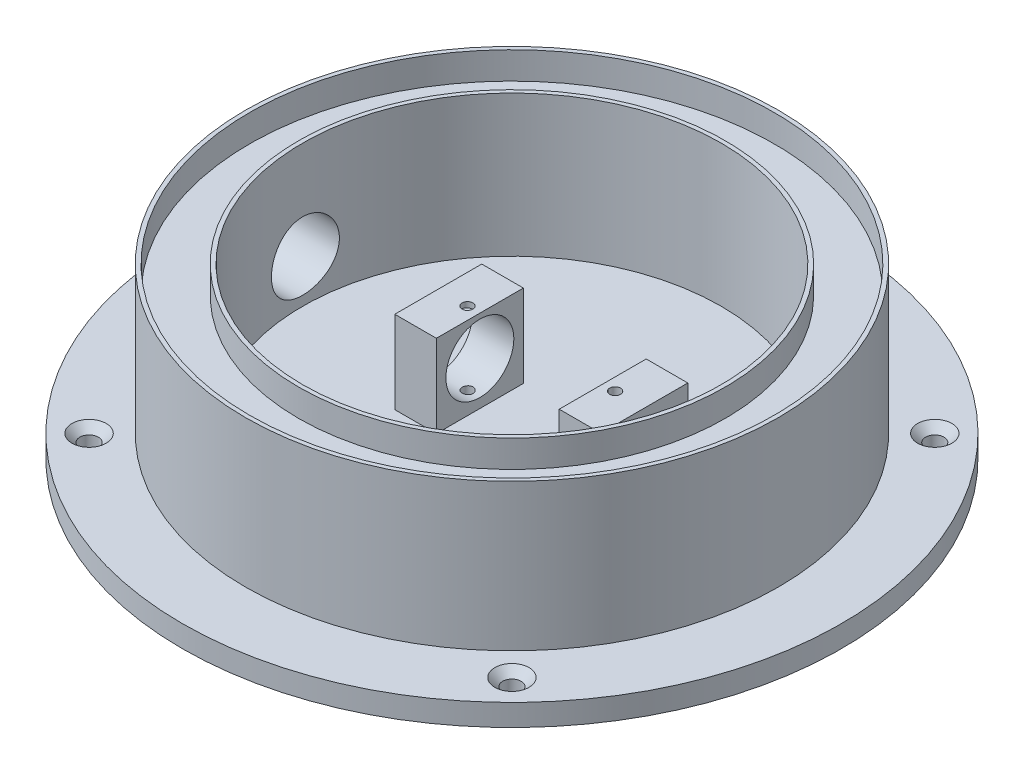
SolidWorks part; units mm, degrees
other "Markup1"
sketch "Sketch25" plane through (60.625, 46, 60.625) normal (0.2544, 0.6682, 0.6991) x (0.7838, 0.2809, -0.5538)
ref_plane "Front Plane" through (0, 0, 0) normal (0, 0, 1) x (1, 0, 0)
ref_plane "Top Plane" through (0, 0, 0) normal (0, 1, 0) x (1, 0, 0)
ref_plane "Right Plane" through (0, 0, 0) normal (1, 0, 0) x (0, 0, -1)
sketch "Sketch1" plane through (0, 0, 0) normal (0, 1, 0) x (1, 0, 0)
  circle A0 centre (0, 0) radius 60.625
  circle A1 centre (0, 0) radius 45
  dimension "D1" = 121.25
  dimension "D2" = 90
extrude "Boss-Extrude1" add sketch "Sketch1" along normal blind 4 contours A0
sketch "Sketch2" plane through (0, 4, 0) normal (0, 1, 0) x (1, 0, 0)
  circle A0 centre (0, 0) radius 45 construction
  circle A1 centre (0, 0) radius 45
  circle A2 centre (0, 0) radius 49
  dimension "D2" = 98
  dimension "D3" = 90
extrude "Boss-Extrude2" add sketch "Sketch2" along normal blind 27
sketch "Sketch4" plane through (0, 0, 0) normal (0, 0, 1) x (1, 0, 0)
  line L0 (-13.55, 4) -> (-5.9, 4)
  line L23 (-5.9, 20.2) -> (-5.9, 4)
  line L25 (16.7, 4) -> (16.7, 20.2)
  line L34 (-13.55, 20.2) -> (-5.9, 20.2)
  line L35 (16.7, 4) -> (24.35, 4)
  line L36 (16.7, 20.2) -> (24.35, 20.2)
  line L37 (24.35, 20.2) -> (24.35, 4)
  line L40 (-13.55, 20.2) -> (-13.55, 4)
  line L41 (60.625, 4) -> (-60.625, 4) construction
  dimension "D1" = 16.2
  dimension "D2" = 22.6
  dimension "D3" = 7.65
  dimension "D4" = 7.65
  dimension "D5" = 16.2
extrude "Boss-Extrude4" add sketch "Sketch4" along normal mid plane 16
sketch "Sketch5" plane through (0, 0, 0) normal (0, -1, 0) x (1, 0, 0)
  circle A2 centre (0, 0) radius 45
  circle M2 centre (0, 0) radius 45
extrude "Boss-Extrude5" add sketch "Sketch5" against normal blind 5 contours M2
sketch "Sketch18" plane through (0, 31, 0) normal (0, 1, 0) x (1, 0, 0)
  circle A0 centre (0, 0) radius 38.5
  circle A1 centre (0, 0) radius 45.1137
extrude "Boss-Extrude6" add sketch "Sketch18" against normal up to surface (31 mm away) from offset 0 up to face at (0, 0, 60.625)
sketch "Sketch27" plane through (0, 20.2, 0) normal (0, 1, 0) x (1, 0, 0)
  line L0 (-8.175, 0) -> (-5.9, 0) construction
  line L1 (-5.9, -8) -> (-5.9, 8) construction
  line L2 (18.975, 0) -> (16.7, 0) construction
  line L3 (16.7, -8) -> (16.7, 8) construction
  circle A0 centre (-8.175, 0) radius 1
  circle A1 centre (18.975, 0) radius 1
  dimension "D1" = 27.15
ref_plane "Plane2" through (49, 0, 0) normal (1, 0, 0) x (0, 0, -1)
sketch "Sketch11" plane through (49, 0, 0) normal (1, 0, 0) x (0, 0, -1)
  circle A0 centre (0, 13) radius 6.25
  dimension "D1" = 12.5
  dimension "D2" = 13
extrude "Cut-Extrude8" cut sketch "Sketch11" against normal through all from offset 35 offset against normal yes
sketch "Sketch14" plane through (0, 4, 0) normal (0, 1, 0) x (1, 0, 0)
  circle A0 centre (-38.8909, 38.8909) radius 1.5
  circle A1 centre (38.8909, 38.8909) radius 1.5
  circle A2 centre (38.8909, -38.8909) radius 1.5
  circle A3 centre (-38.8909, -38.8909) radius 1.5
  point P15 (0, 0)
  dimension "D1" = 3
  dimension "D4" = 4
hole_wizard "CSK for M3 Countersunk Flat Head Screw1" positions "Sketch15" profile "Sketch17" countersink size "M3" standard "DIN" end condition up to next
sketch "Sketch15" plane through (0, 4, 0) normal (0, 1, 0) x (1, 0, 0)
  point P0 (-38.8909, 38.8909)
  point P3 (-38.8909, -38.8909)
  point P6 (38.8909, -38.8909)
  point P9 (38.8909, 38.8909)
sketch "Sketch17" plane through (-38.8909, 4, -38.8909) normal (1, 0, 0) x (0, 0, 1)
  line L0 (0, 0) -> (0, 4)
  line L1 (0, 4) -> (1.7, 4)
  line L2 (1.7, 4) -> (1.7, 1.45)
  line L3 (1.7, 1.45) -> (3.15, 0)
  line L5 (3.15, 0) -> (0, 0)
  line L6 (-1.7, 1.45) -> (-3.15, 0) construction
  line L11 (0, -6.35) -> (0, 107.95) construction
  dimension "Thru Hole Dia." = 3.4
  dimension "Thru Hole Depth" = 4
  dimension "Near C'Sink Dia." = 6.3
  dimension "Near C'Sink Angle" = 90
extrude "Cut-Extrude11" cut sketch "Sketch27" against normal blind 16
sketch "Sketch28" plane through (0, 31, 0) normal (0, 1, 0) x (1, 0, 0)
  circle A1 centre (0, 0) radius 48.25
  circle A3 centre (0, 0) radius 39.25
extrude "Cut-Extrude12" cut sketch "Sketch28" against normal blind 5
